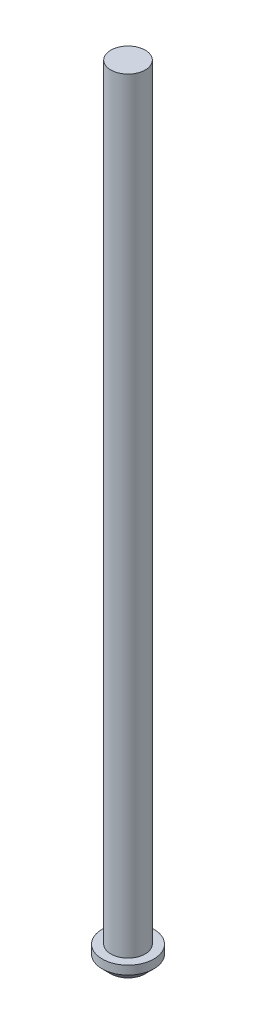
SolidWorks part; units mm, degrees
ref_plane "Front Plane" through (0, 0, 0) normal (0, 0, 1) x (1, 0, 0)
ref_plane "Top Plane" through (0, 0, 0) normal (0, 1, 0) x (1, 0, 0)
ref_plane "Right Plane" through (0, 0, 0) normal (1, 0, 0) x (0, 0, -1)
sketch "Sketch1" plane through (0, 0, 0) normal (0, 1, 0) x (1, 0, 0)
  circle A0 centre (0, 0) radius 2
  dimension "D1" = 4
extrude "Boss-Extrude1" add sketch "Sketch1" along normal blind 89
sketch "Sketch2" plane through (0, 0, 0) normal (0, -1, 0) x (1, 0, 0)
  circle A0 centre (0, 0) radius 3
  dimension "D1" = 6
extrude "Boss-Extrude2" add sketch "Sketch2" along normal blind 2
chamfer "Chamfer1" distance 1 angle 45 1 edges at (0, -2, -3)
